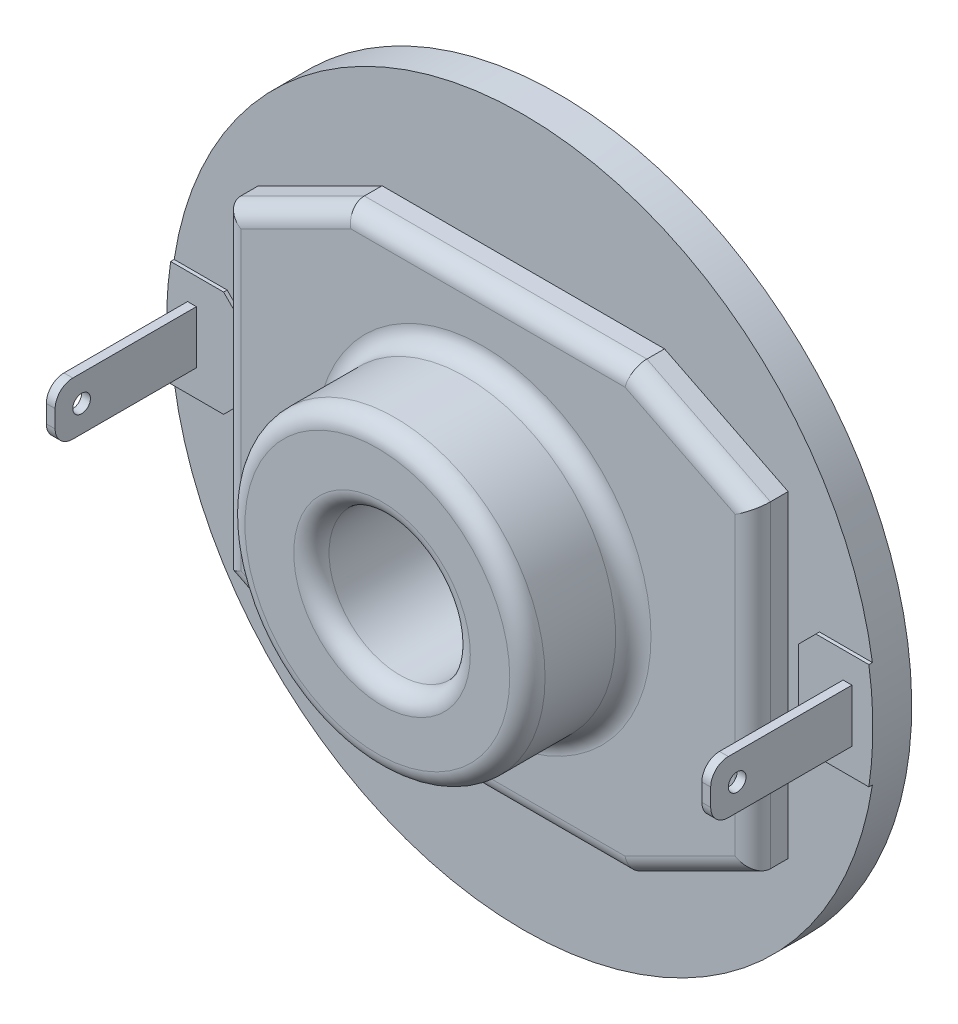
SolidWorks part; units mm, degrees
material "Nickel silver 65-12, UNS C75700"
ref_plane "Front Plane" through (0, 0, 0) normal (0, 0, 1) x (1, 0, 0)
ref_plane "Top Plane" through (0, 0, 0) normal (0, 1, 0) x (1, 0, 0)
ref_plane "Right Plane" through (0, 0, 0) normal (1, 0, 0) x (0, 0, -1)
sketch "Sketch1" plane through (0, 0, 0) normal (0, 0, 1) x (1, 0, 0)
  line L0 (-15, 9) -> (-8, 12.5)
  line L1 (-8, 12.5) -> (8, 12.5)
  line L2 (-15, 9) -> (-15, -9)
  line L3 (-8, -12.5) -> (8, -12.5)
  line L4 (15, 9) -> (15, -9)
  line L5 (-15, 12.5) -> (15, -12.5) construction
  line L6 (-15, -12.5) -> (15, 12.5) construction
  line L7 (8, 12.5) -> (15, 9)
  line L8 (15, -9) -> (8, -12.5)
  line L9 (-15, -9) -> (-8, -12.5)
  dimension "D2" = 30
  dimension "D3" = 25
  dimension "D4" = 7
  dimension "D5" = 3.5
  dimension "D6" = 7
  dimension "D7" = 3.5
  dimension "D8" = 3.5
  dimension "D9" = 7
  dimension "D10" = 7
  dimension "D11" = 3.5
extrude "Boss-Extrude1" add sketch "Sketch1" along normal blind 2
sketch "Sketch2" plane through (0, 0, 0) normal (0, 0, -1) x (-1, 0, 0)
  circle A0 centre (0, 0) radius 20
  dimension "D1" = 40
extrude "Boss-Extrude2" add sketch "Sketch2" along normal blind 2
fillet "Fillet1" radius 1 8 edges at (11.5, 10.75, 2) (15, 0, 2) (11.5, -10.75, 2) (0, -12.5, 2) (-11.5, -10.75, 2) (-15, 0, 2) (-11.5, 10.75, 2) (0, 12.5, 2)
sketch "Sketch3" plane through (0, 0, 2) normal (0, 0, 1) x (1, 0, 0)
  circle A0 centre (-0.2661, 0) radius 8.5
  dimension "D1" = 17
extrude "Boss-Extrude3" add sketch "Sketch3" along normal blind 6
sketch "Sketch4" plane through (0, 0, 8) normal (0, 0, 1) x (1, 0, 0)
  circle A0 centre (0, 0) radius 4
  dimension "D1" = 8
extrude "Cut-Extrude1" cut sketch "Sketch4" against normal through all
fillet "Fillet2" radius 1 3 edges at (4, 0, 8) (8.2339, 0, 8) (-8.7661, 0, 2)
sketch "Sketch5" plane through (0, 0, 0) normal (0, 0, 1) x (1, 0, 0)
  line L0 (-19.7737, 3) -> (-16.7737, 3)
  line L1 (-16.7737, 3) -> (-15.7737, 2)
  line L2 (-15.7737, 2) -> (-15.7737, -2)
  line L3 (-15.7737, -2) -> (-16.7737, -3)
  line L4 (-16.7737, -3) -> (-19.7737, -3)
  line L5 (0, 0) -> (0, 3.3742) construction
  line L6 (19.7737, 3) -> (16.7737, 3)
  line L7 (16.7737, 3) -> (15.7737, 2)
  line L8 (15.7737, 2) -> (15.7737, -2)
  line L9 (15.7737, -2) -> (16.7737, -3)
  line L10 (16.7737, -3) -> (19.7737, -3)
  circle A0 centre (0, 0) radius 20 construction
  arc A1 (-19.7737, 3) -> (-19.7737, -3) centre (0, 0) ccw
  arc A2 (19.7737, 3) -> (19.7737, -3) centre (0, 0) cw
  dimension "D1" = 3
  dimension "D2" = 3
  dimension "D3" = 1
  dimension "D4" = 1
  dimension "D5" = 3
  dimension "D6" = 3
extrude "Boss-Extrude4" add sketch "Sketch5" along normal blind 0.2
sketch "Sketch6" plane through (0, 0, 0.2) normal (0, 0, 1) x (1, 0, 0)
  line L0 (0, 0) -> (0, 3.1772) construction
  line L1 (-18.8142, 1.5128) -> (-18.3142, 1.5128)
  line L2 (-18.8142, 1.5128) -> (-18.8142, -1.4872)
  line L3 (-18.8142, -1.4872) -> (-18.3142, -1.4872)
  line L4 (-18.3142, 1.5128) -> (-18.3142, -1.4872)
  line L5 (-18.8142, 1.5128) -> (-18.3142, -1.4872) construction
  line L6 (-18.8142, -1.4872) -> (-18.3142, 1.5128) construction
  line L7 (18.8142, -1.4872) -> (18.3142, -1.4872)
  line L8 (18.3142, 1.5128) -> (18.3142, -1.4872)
  line L9 (18.8142, 1.5128) -> (18.3142, 1.5128)
  line L10 (18.8142, 1.5128) -> (18.8142, -1.4872)
  point P0 (-18.5642, 0.0128)
  dimension "D1" = 3
  dimension "D2" = 0.5
extrude "Boss-Extrude5" add sketch "Sketch6" along normal blind 8
fillet "Fillet3" radius 1 4 edges at (18.5642, 1.5128, 8.2) (18.5642, -1.4872, 8.2) (-18.5642, -1.4872, 8.2) (-18.5642, 1.5128, 8.2)
sketch "Sketch7" plane through (-18.8142, 0, 0) normal (-1, 0, 0) x (0, 0, 1)
  line L0 (8.2, 0.5128) -> (8.2, -0.4872) construction
  line L1 (7.2, 1.5128) -> (0.2, 1.5128) construction
  circle A0 centre (6.7, 0.0128) radius 0.5
  dimension "D1" = 1
  dimension "D2" = 1.5
  dimension "D3" = 1.5
extrude "Cut-Extrude2" cut sketch "Sketch7" against normal blind 4
sketch "Sketch8" plane through (18.8142, 0, 0) normal (1, 0, 0) x (0, 0, -1)
  line L0 (-8.2, -0.4872) -> (-8.2, 0.5128) construction
  line L1 (-7.2, -1.4872) -> (-0.2, -1.4872) construction
  circle A0 centre (-6.7, 0.0128) radius 0.5
  dimension "D1" = 1
  dimension "D2" = 1.5
  dimension "D3" = 1.5
extrude "Cut-Extrude3" cut sketch "Sketch8" against normal blind 4
